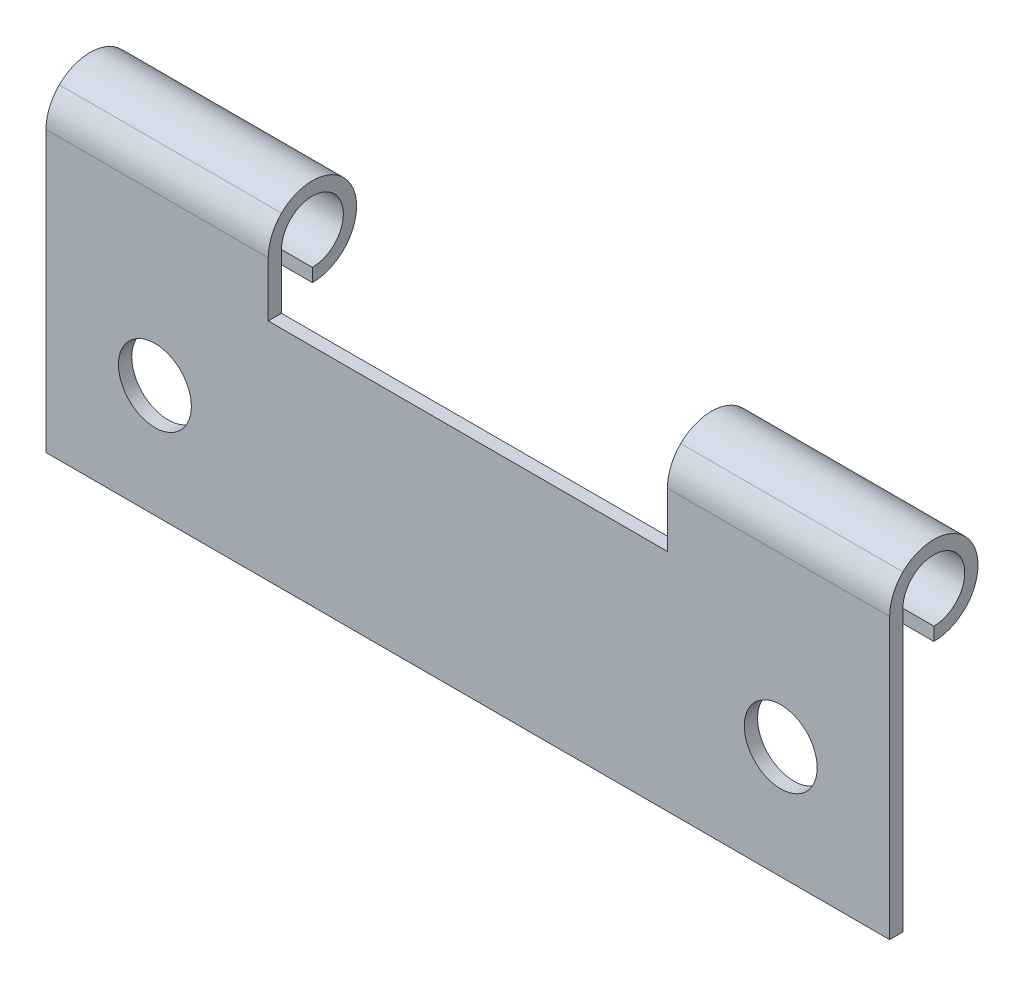
SolidWorks part; units mm, degrees
ref_plane "Front Plane" through (0, 0, 0) normal (0, 0, 1) x (1, 0, 0)
ref_plane "Top Plane" through (0, 0, 0) normal (0, 1, 0) x (1, 0, 0)
ref_plane "Right Plane" through (0, 0, 0) normal (1, 0, 0) x (0, 0, -1)
sketch "Sketch1" plane through (0, 0, 0) normal (0, 0, 1) x (1, 0, 0)
  line L1 (0, 0) -> (38.19, 0)
  line L2 (0, 0) -> (0, -10.19)
  line L3 (0, -10.19) -> (38.19, -10.19)
  line L4 (38.19, 0) -> (38.19, -10.19)
  dimension "D1" = 10.19
  dimension "D2" = 38.19
extrude "Boss-Extrude1" add sketch "Sketch1" along normal blind 0.6
sketch "Sketch2" plane through (0, 0, 0) normal (0, 1, 0) x (1, 0, 0)
  line L0 (38.19, -0.6) -> (0, -0.6) construction
  line L1 (0, 0) -> (10.06, 0)
  line L2 (0, 0) -> (0, -0.6)
  line L3 (0, -0.6) -> (10.06, -0.6)
  line L4 (10.06, 0) -> (10.06, -0.6)
  line L5 (38.19, 0) -> (0, 0) construction
  line L6 (38.19, -0.6) -> (28.13, -0.6)
  line L7 (38.19, -0.6) -> (38.19, 0)
  line L8 (38.19, 0) -> (28.13, 0)
  line L9 (28.13, -0.6) -> (28.13, 0)
  dimension "D1" = 10.06
  dimension "D2" = 10.06
extrude "Boss-Extrude2" add sketch "Sketch2" along normal blind 4.5
sketch "Sketch4" plane through (38.19, 0, 0) normal (1, 0, 0) x (0, 0, -1)
  line L0 (-0.6, 4.5) -> (0, 4.5) construction
  line L1 (-0.6, -10.19) -> (-0.6, 4.5) construction
  line L2 (0, 2.5) -> (-0.6, 2.5)
  line L3 (1.4, 1.1) -> (1.4, 0.5)
  arc A0 (1.4, 0.5) -> (-0.6, 2.5) centre (1.4, 2.5) ccw
  arc A1 (1.4, 1.1) -> (0, 2.5) centre (1.4, 2.5) ccw
  dimension "D1" = 4
extrude "Boss-Extrude3" add sketch "Sketch4" against normal up to surface (10.06 mm away) up to face at (28.13, 2.25, 0.3)
sketch "Sketch5" plane through (0, 0, 0) normal (-1, 0, 0) x (0, 0, 1)
  line L0 (0, 2.5) -> (0.6, 2.5)
  line L1 (-1.4, 1.1) -> (-1.4, 0.5)
  line L6 (0, 4.5) -> (0, 3.9283)
  line L7 (-1.4, 0.5) -> (-1.4, 1.1)
  line L8 (0, 2.5) -> (0, 0)
  line L9 (0, 0) -> (0.6, 0)
  line L10 (0.6, 0) -> (0.6, 4.5)
  line L11 (0.6, 4.5) -> (0, 4.5)
  line L12 (0, 4.5) -> (0, 3.9283)
  line L13 (-1.4, 0.5) -> (-1.4, 1.1)
  line L14 (0, 1.8717) -> (0, 0)
  line L15 (0, 0) -> (0.6, 0)
  line L16 (0.6, 2.5) -> (0.6, 4.5)
  line L17 (0.6, 4.5) -> (0, 4.5)
  arc A0 (0.6, 2.5) -> (-1.4, 0.5) centre (-1.4, 2.5) ccw
  arc A1 (0, 2.5) -> (-1.4, 1.1) centre (-1.4, 2.5) ccw
  arc A2 (0, 3.9283) -> (-1.4, 0.5) centre (-1.4, 2.5) ccw
  arc A3 (0, 2.5) -> (-1.4, 1.1) centre (-1.4, 2.5) ccw
  arc A4 (0, 3.9283) -> (-1.4, 0.5) centre (-1.4, 2.5) ccw
  arc A5 (0, 2.5) -> (-1.4, 1.1) centre (-1.4, 2.5) ccw
  line M11 (0, 4.5) -> (0, -10.19)
  dimension "D1" = 0
extrude "Boss-Extrude4" add sketch "Sketch5" against normal up to surface (10.06 mm away) contours A1 A0 L1 M11 | L0 A0 M11 up to face at (10.06, 2.25, 0.3)
sketch "Sketch6" plane through (0, 0, 0) normal (-1, 0, 0) x (0, 0, 1)
  line L0 (0, 3.9283) -> (0, 4.5)
  line L1 (0, 4.5) -> (0.6, 4.5)
  line L2 (0.6, 4.5) -> (0.6, -10.19) construction
  line L3 (0, 4.5) -> (0.6, 4.5) construction
  line L4 (0.6, 2.4767) -> (0.6, 4.5)
  arc A0 (0, 3.9283) -> (0.6, 2.4767) centre (-1.456, 2.4767) cw
extrude "Cut-Extrude1" cut sketch "Sketch6" against normal through all
sketch "Sketch7" plane through (0, 0, 0) normal (0, 0, -1) x (-1, 0, 0)
  line L1 (0, -10.19) -> (-38.19, -10.19) construction
  line L2 (0, 2.5) -> (0, -10.19) construction
  line L3 (-38.19, -10.19) -> (-38.19, 2.5) construction
  circle A0 centre (-33.26, -5.095) radius 1.65
  circle A1 centre (-4.93, -5.095) radius 1.65
  dimension "D1" = 3.3
  dimension "D2" = 3.3
  dimension "D3" = 5.095
  dimension "D4" = 5.095
  dimension "D5" = 4.93
  dimension "D6" = 4.93
extrude "Cut-Extrude2" cut sketch "Sketch7" against normal blind 10.01
